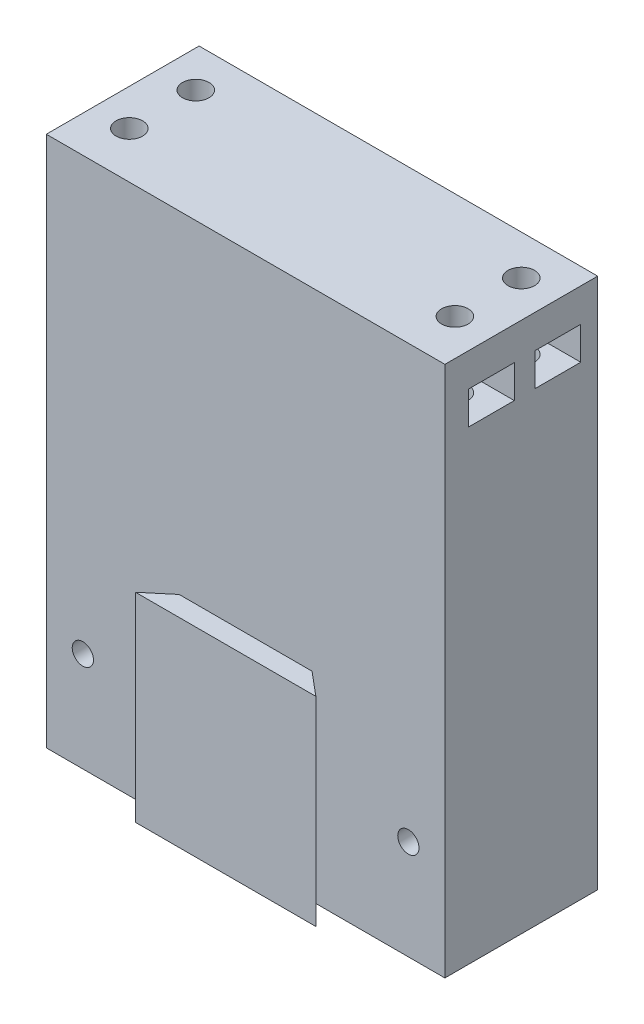
SolidWorks part; units mm, degrees
material "6061 合金"
ref_plane "前视基准面" through (0, 0, 0) normal (0, 0, 1) x (1, 0, 0)
ref_plane "上视基准面" through (0, 0, 0) normal (0, 1, 0) x (1, 0, 0)
ref_plane "右视基准面" through (0, 0, 0) normal (1, 0, 0) x (0, 0, -1)
sketch "草图1" plane through (0, 0, 0) normal (0, 0, 1) x (1, 0, 0)
  line L1 (-30, 40) -> (30, 40)
  line L2 (-30, 40) -> (-30, -40)
  line L3 (-30, -40) -> (30, -40)
  line L4 (30, 40) -> (30, -40)
  line L5 (-30, 40) -> (30, -40) construction
  line L6 (-30, -40) -> (30, 40) construction
  point P0 (0, 0)
  dimension "D1" = 80
  dimension "D2" = 60
extrude "凸台-拉伸1" add sketch "草图1" along normal blind 23
sketch "草图2" plane through (30, 0, 0) normal (1, 0, 0) x (0, 0, -1)
  line L1 (-19.8, 24) -> (-19.8, 30)
  line L2 (-19.8, 24) -> (-2.6, 24)
  line L3 (-2.6, 24) -> (-2.6, 30)
  line L4 (-19.8, 30) -> (-2.6, 30)
  line L6 (0, -40) -> (0, 40) construction
  line L7 (-23, 40) -> (0, 40) construction
  dimension "D1" = 2.6
  dimension "D2" = 6
  dimension "D3" = 10
  dimension "D4" = 17.2
extrude "切除-拉伸1" [suppressed] cut sketch "草图2" against normal blind 10
sketch "草图3" plane through (0, 40, 0) normal (0, 1, 0) x (1, 0, 0)
  line L0 (24.5, -6) -> (24.5, -16) construction
  line L1 (30, 0) -> (-30, 0) construction
  line L2 (30, -23) -> (30, 0) construction
  line L3 (0, 0) -> (0, -23) construction
  line L4 (30, -23) -> (-30, -23) construction
  circle A0 centre (24.5, -6) radius 2
  circle A1 centre (24.5, -16) radius 2
  dimension "D1" = 4
  dimension "D2" = 4
  dimension "D3" = 10
  dimension "D4" = 6
  dimension "D5" = 5.5
extrude "切除-拉伸2" cut sketch "草图3" against normal blind 25
mirror "镜向1" about plane through (0, 0, 0) normal (1, 0, 0) of "切除-拉伸1", "切除-拉伸2"
sketch "草图4" plane through (0, 40, 0) normal (0, 1, 0) x (1, 0, 0)
  line L0 (0, 0) -> (0, -37.8762) construction
  line L1 (10, -23) -> (13.5753, -26)
  line L2 (30, -23) -> (-30, -23) construction
  line L3 (13.5753, -26) -> (-13.5753, -26)
  line L4 (0, -26) -> (0, -23)
  line L5 (-10, -23) -> (10, -23)
  line L6 (-10, -23) -> (-13.5753, -26)
  line M13 (-30, -23) -> (30, -23)
  dimension "D1" = 40
  dimension "D2" = 3
  dimension "D3" = 10
extrude "凸台-拉伸2" add sketch "草图4" against normal blind 30 from offset 50 contours L4 L3 L1 M13 | L6 L3 L4 M13 offset against normal yes
sketch "草图5" plane through (0, 0, 0) normal (0, 0, -1) x (-1, 0, 0)
  line L0 (0, 0) -> (0, -40) construction
  line L1 (30, -40) -> (-30, -40) construction
  circle A0 centre (-24.5, -25) radius 1.6
  circle A1 centre (24.5, -25) radius 1.6
  dimension "D1" = 3.2
  dimension "D2" = 49
  dimension "D3" = 15
extrude "切除-拉伸3" cut sketch "草图5" against normal through all
sketch "草图7" plane through (0, 40, 0) normal (0, 1, 0) x (1, 0, 0)
  line L0 (30, -23) -> (30, 0) construction
  line L1 (30, -9.45) -> (26.4919, -9.45)
  line L2 (30, -9.45) -> (30, -2.55)
  line L3 (30, -2.55) -> (26.4919, -2.55)
  line L4 (26.4919, -9.45) -> (26.4919, -2.55) construction
  line L5 (24.5, -6) -> (30, -6) construction
  line L6 (0, 0) -> (0, -23) construction
  line L7 (26.4919, -2.55) -> (22.5081, -2.55)
  line L8 (22.5081, -2.55) -> (20.5163, -6)
  line L9 (20.5163, -6) -> (22.5081, -9.45)
  line L10 (22.5081, -9.45) -> (26.4919, -9.45)
  line L11 (26.4919, -9.45) -> (28.4837, -6)
  line L12 (28.4837, -6) -> (26.4919, -2.55)
  line L13 (30, 0) -> (-30, 0) construction
  line L14 (-10, -23) -> (10, -23) construction
  line L15 (-22.5081, -9.45) -> (-26.4919, -9.45)
  line L16 (-30, -9.45) -> (-26.4919, -9.45)
  line L17 (-30, -9.45) -> (-30, -2.55)
  line L18 (-30, -2.55) -> (-26.4919, -2.55)
  line L19 (-26.4919, -2.55) -> (-22.5081, -2.55)
  line L20 (-22.5081, -2.55) -> (-20.5163, -6)
  line L21 (-20.5163, -6) -> (-22.5081, -9.45)
  circle A1 centre (24.5, -6) radius 3.45 construction
  point P22 (26.6413, -9.45)
  circle M12 centre (-24.5, -6) radius 2
  circle M14 centre (24.5, -6) radius 2
  line M17 (-30, 0) -> (-30, -23)
  line M19 (30, -23) -> (30, 0)
  dimension "D1" = 6.9
extrude "切除-拉伸4" cut sketch "草图7" against normal blind 4.95 from offset 5 contours L21 L20 L19 L18 L16 L15 M17 M12 | L11 L12 L7 L8 L9 L10 M14 | L12 L11 L1 L3 M19 offset against normal yes
pattern_linear "阵列(线性)1" count 2 spacing 10 along (0, 0, 1) of "切除-拉伸4"
